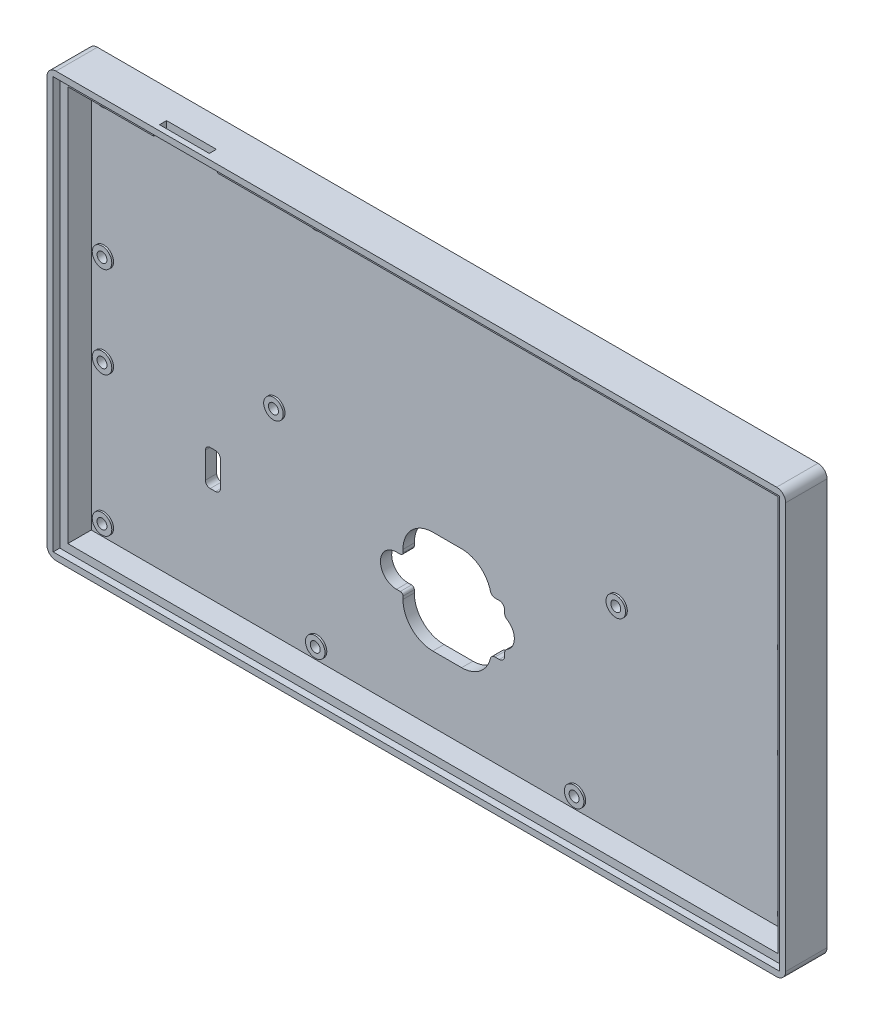
SolidWorks part; units mm, degrees
ref_plane "Front Plane" through (0, 0, 0) normal (0, 0, 1) x (1, 0, 0)
ref_plane "Top Plane" through (0, 0, 0) normal (0, 1, 0) x (1, 0, 0)
ref_plane "Right Plane" through (0, 0, 0) normal (1, 0, 0) x (0, 0, -1)
sketch "PCB" plane through (0, 0, 0) normal (0, 0, 1) x (1, 0, 0)
  line L0 (96.2635, 52.0314) -> (101.8921, 52.0314) construction
  line L1 (-101.8921, 57.66) -> (101.8921, 57.66) construction
  line L2 (-101.8921, 57.66) -> (-101.8921, -57.66) construction
  line L3 (-101.8921, -57.66) -> (101.8921, -57.66) construction
  line L4 (101.8921, 57.66) -> (101.8921, -57.66) construction
  line L5 (-101.8921, 57.66) -> (101.8921, -57.66) construction
  line L6 (-101.8921, -57.66) -> (101.8921, 57.66) construction
  line L7 (96.2635, 52.0314) -> (96.2635, 57.66) construction
  line L8 (-96.2635, 52.0314) -> (-101.8921, 52.0314) construction
  line L9 (-96.2635, -52.0314) -> (-96.2635, -57.66) construction
  line L10 (-92.8243, 0) -> (-92.8243, 32.1584) construction
  line L11 (-98.8568, 38.1909) -> (-86.7918, 38.1909)
  line L12 (-98.8568, 38.1909) -> (-98.8568, 26.1259)
  line L13 (-98.8568, 26.1259) -> (-86.7918, 26.1259)
  line L14 (-86.7918, 38.1909) -> (-86.7918, 26.1259)
  line L15 (-98.8568, 38.1909) -> (-86.7918, 26.1259) construction
  line L16 (-98.8568, 26.1259) -> (-86.7918, 38.1909) construction
  line L17 (-98.8568, 6.0325) -> (-86.7918, 6.0325)
  line L18 (-98.8568, 6.0325) -> (-98.8568, -6.0325)
  line L19 (-98.8568, -6.0325) -> (-86.7918, -6.0325)
  line L20 (-86.7918, 6.0325) -> (-86.7918, -6.0325)
  line L21 (-98.8568, 6.0325) -> (-86.7918, -6.0325) construction
  line L22 (-98.8568, -6.0325) -> (-86.7918, 6.0325) construction
  line L23 (-98.8568, -26.1259) -> (-86.7918, -26.1259)
  line L24 (-98.8568, -26.1259) -> (-98.8568, -38.1909)
  line L25 (-98.8568, -38.1909) -> (-86.7918, -38.1909)
  line L26 (-86.7918, -26.1259) -> (-86.7918, -38.1909)
  line L27 (-98.8568, -26.1259) -> (-86.7918, -38.1909) construction
  line L28 (-98.8568, -38.1909) -> (-86.7918, -26.1259) construction
  line L29 (86.7918, 38.1909) -> (98.8568, 38.1909)
  line L30 (86.7918, 38.1909) -> (86.7918, 26.1259)
  line L31 (86.7918, 26.1259) -> (98.8568, 26.1259)
  line L32 (98.8568, 38.1909) -> (98.8568, 26.1259)
  line L33 (86.7918, 38.1909) -> (98.8568, 26.1259) construction
  line L34 (86.7918, 26.1259) -> (98.8568, 38.1909) construction
  line L35 (86.7918, 6.0325) -> (98.8568, 6.0325)
  line L36 (86.7918, 6.0325) -> (86.7918, -6.0325)
  line L37 (86.7918, -6.0325) -> (98.8568, -6.0325)
  line L38 (98.8568, 6.0325) -> (98.8568, -6.0325)
  line L39 (86.7918, 6.0325) -> (98.8568, -6.0325) construction
  line L40 (86.7918, -6.0325) -> (98.8568, 6.0325) construction
  line L41 (86.7918, -26.1259) -> (98.8568, -26.1259)
  line L42 (86.7918, -26.1259) -> (86.7918, -38.1909)
  line L43 (86.7918, -38.1909) -> (98.8568, -38.1909)
  line L44 (98.8568, -26.1259) -> (98.8568, -38.1909)
  line L45 (86.7918, -26.1259) -> (98.8568, -38.1909) construction
  line L46 (86.7918, -38.1909) -> (98.8568, -26.1259) construction
  line L47 (-92.8243, 0) -> (-92.8243, -32.1584) construction
  line L48 (-92.8243, 32.1584) -> (-101.8921, 32.1584) construction
  line L49 (92.8243, 32.1584) -> (101.8921, 32.1584) construction
  line L50 (-3.114, -17.4952) -> (-3.114, -27.7568) construction
  circle A0 centre (-96.2635, 52.0314) radius 0.9995
  circle A1 centre (-96.2635, -52.0314) radius 0.9995
  circle A2 centre (96.2635, -52.0314) radius 0.9995
  circle A3 centre (96.2635, 52.0314) radius 0.9995
  circle A4 centre (-3.114, -17.4952) radius 1.9939
  circle A5 centre (-3.114, -27.7568) radius 1.9939
  point P0 (0, 0)
  point P14 (-92.8243, 32.1584)
  point P23 (-92.8243, 0)
  point P28 (-92.8243, -32.1584)
  point P33 (92.8243, 32.1584)
  point P38 (92.8243, 0)
  point P43 (92.8243, -32.1584)
  point P54 (0.1092, -22.626)
  point P55 (-7.5006, -22.626)
  point P60 (-3.114, -22.626)
  dimension "D4" = 1.999
  dimension "D14" = 3.9878
  dimension "D1" = 203.7842
  dimension "D2" = 115.32
  dimension "D3" = 5.6286
  dimension "D5" = 25.5016
  dimension "D6" = 25.5016
  dimension "D7" = 9.0678
  dimension "D8" = 12.065
  dimension "D9" = 102.0013
  dimension "D10" = 35.034
  dimension "D11" = 7.6098
  dimension "D12" = 5.1308
  dimension "D13" = 3.2233
sketch "DT_plug" plane through (0, 0, 0) normal (0, 0, 1) x (1, 0, 0)
  line L0 (29.2774, -40.0231) -> (29.2774, -5.0981) construction
  dimension "D1" = 34.925
sketch "display_screen" plane through (0, 0, 0) normal (0, 0, 1) x (1, 0, 0)
  line L1 (-80.3275, 46.3296) -> (83.7565, 46.3296) construction
  line L2 (-80.3275, 46.3296) -> (-80.3275, -50.9016) construction
  line L3 (-80.3275, -50.9016) -> (83.7565, -50.9016) construction
  line L4 (83.7565, 46.3296) -> (83.7565, -50.9016) construction
  line L5 (-78.2955, 44.2976) -> (78.2955, 44.2976) construction
  line L6 (-78.2955, 44.2976) -> (-78.2955, -44.2976) construction
  line L7 (-78.2955, -44.2976) -> (78.2955, -44.2976) construction
  line L8 (78.2955, 44.2976) -> (78.2955, -44.2976) construction
  point P8 (0, 44.2976)
  point P10 (-78.2955, 0)
  dimension "D1" = 164.084
  dimension "D2" = 97.2312
  dimension "D3" = 6.604
  dimension "D4" = 2.032
  dimension "D5" = 2.032
  dimension "D6" = 5.461
ref_plane "back_of_PCB" through (0, 0, -1.8542) normal (0, 0, 1) x (1, 0, 0)
ref_plane "back_PCB_clearance" through (0, 0, -8.4582) normal (0, 0, 1) x (1, 0, 0)
sketch "Sketch4" plane through (0, 0, 0) normal (0, 0, 1) x (1, 0, 0)
  line L0 (-102.1461, 57.8886) -> (-102.1461, 59.6386) construction
  line L1 (-102.1461, 57.8886) -> (102.1461, 57.8886)
  line L2 (-102.1461, 57.8886) -> (-102.1461, -57.8886)
  line L3 (-102.1461, -57.8886) -> (102.1461, -57.8886)
  line L4 (102.1461, 57.8886) -> (102.1461, -57.8886)
  line L5 (-103.8961, 59.6386) -> (103.8961, 59.6386)
  line L6 (-103.8961, 59.6386) -> (-103.8961, -59.6386)
  line L7 (-103.8961, -59.6386) -> (103.8961, -59.6386)
  line L8 (103.8961, 59.6386) -> (103.8961, -59.6386)
  line L9 (-102.1461, 57.8886) -> (-103.8961, 57.8886) construction
  line L10 (102.1461, -57.8886) -> (102.1461, -59.6386) construction
  line L11 (102.1461, -57.8886) -> (103.8961, -57.8886) construction
  line L12 (-101.8921, 57.66) -> (101.8921, 57.66) construction
  line L13 (-101.8921, 57.66) -> (-101.8921, -57.66) construction
  line L14 (101.8921, 57.66) -> (101.8921, -57.66) construction
  line L15 (-101.8921, -57.66) -> (101.8921, -57.66) construction
  dimension "D1" = 1.75
  dimension "D2" = 0.2286
  dimension "D3" = 0.254
  dimension "D4" = 0.254
  dimension "D5" = 0.2286
extrude "Boss-Extrude1" add sketch "Sketch4" against normal up to surface (1.8542 mm away) up to plane "back_of_PCB"
sketch "Sketch5" plane through (0, 0, -1.8542) normal (0, 0, -1) x (-1, 0, 0)
  line L1 (-103.8961, 59.6386) -> (103.8961, 59.6386)
  line L2 (-103.8961, 59.6386) -> (-103.8961, -59.6386)
  line L3 (-103.8961, -59.6386) -> (103.8961, -59.6386)
  line L4 (103.8961, 59.6386) -> (103.8961, -59.6386)
  line L6 (101.8921, 57.66) -> (-101.8921, 57.66) construction
  line L7 (-99.8931, 55.661) -> (99.8931, 55.661)
  line L8 (-99.8931, 55.661) -> (-99.8931, -55.661)
  line L9 (-99.8931, -55.661) -> (99.8931, -55.661)
  line L10 (99.8931, 55.661) -> (99.8931, -55.661)
  line L11 (-99.8931, 55.661) -> (-99.8931, 57.66) construction
  line L12 (-99.8931, 55.661) -> (-101.8921, 55.661) construction
  line L13 (-101.8921, 57.66) -> (-101.8921, -57.66) construction
  line L14 (99.8931, -55.661) -> (101.8921, -55.661) construction
  line L15 (101.8921, 57.66) -> (101.8921, -57.66) construction
  line L16 (99.8931, -55.661) -> (99.8931, -57.66) construction
  line L17 (101.8921, -57.66) -> (-101.8921, -57.66) construction
  dimension "D1" = 1.999
extrude "Boss-Extrude2" add sketch "Sketch5" along normal up to surface (6.604 mm away) up to plane "back_PCB_clearance"
sketch "Sketch6" plane through (0, 0, -8.4582) normal (0, 0, -1) x (-1, 0, 0)
  line L0 (11.7018, -27.9219) -> (11.7018, -28.722) construction
  line L1 (-103.8961, 59.6386) -> (103.8961, 59.6386)
  line L2 (-103.8961, 59.6386) -> (-103.8961, -59.6386)
  line L3 (-103.8961, -59.6386) -> (103.8961, -59.6386)
  line L4 (103.8961, 59.6386) -> (103.8961, -59.6386)
  line L5 (3.8278, -8.656) -> (-4.2865, -8.656) construction
  line L6 (11.7018, -16.53) -> (11.7018, -17.3301) construction
  line L7 (3.8278, -36.596) -> (-4.2865, -36.596) construction
  line L11 (12.9718, -18.6001) -> (14.0259, -18.6001) construction
  line L13 (12.9718, -26.6519) -> (14.0259, -26.6519) construction
  line L15 (-13.6655, -15.9585) -> (-14.8666, -15.9585) construction
  line L16 (-15.8826, -27.4459) -> (-15.8826, -28.2775) construction
  line L17 (-13.6655, -29.2935) -> (-14.8666, -29.2935) construction
  line L18 (-15.8826, -16.9745) -> (-15.8826, -17.8061) construction
  line L20 (12.2098, -27.9219) -> (12.2098, -28.722)
  line L21 (3.8278, -37.104) -> (-4.2865, -37.104)
  line L22 (-13.6655, -29.8015) -> (-14.8666, -29.8015)
  line L23 (-16.3906, -27.4459) -> (-16.3906, -28.2775)
  line L24 (-16.3906, -16.9745) -> (-16.3906, -17.8061)
  line L25 (-13.6655, -15.4505) -> (-14.8666, -15.4505)
  line L26 (3.8278, -8.148) -> (-4.2865, -8.148)
  line L27 (12.2098, -16.53) -> (12.2098, -17.3301)
  line L28 (12.9718, -18.0921) -> (14.0259, -18.0921)
  line L29 (12.9718, -27.1599) -> (14.0259, -27.1599)
  arc A0 (-16.7989, -19.4311) -> (-16.7989, -25.8209) centre (-14.8666, -22.626) ccw construction
  arc A1 (12.9718, -18.6001) -> (11.7018, -17.3301) centre (12.9718, -17.3301) cw construction
  arc A2 (12.9718, -26.6519) -> (11.7018, -27.9219) centre (12.9718, -27.9219) ccw construction
  arc A3 (14.0259, -26.6519) -> (14.0259, -18.6001) centre (14.0259, -22.626) ccw construction
  arc A4 (11.7018, -28.722) -> (3.8278, -36.596) centre (3.8278, -28.722) cw construction
  arc A5 (11.7018, -16.53) -> (3.8278, -8.656) centre (3.8278, -16.53) ccw construction
  arc A6 (-4.2865, -8.656) -> (-11.9202, -14.5996) centre (-4.2865, -16.53) ccw construction
  arc A7 (-11.9202, -14.5996) -> (-13.6655, -15.9585) centre (-13.6655, -14.1583) cw construction
  arc A8 (-4.2865, -36.596) -> (-11.9202, -30.6524) centre (-4.2865, -28.722) cw construction
  arc A9 (-11.9202, -30.6524) -> (-13.6655, -29.2935) centre (-13.6655, -31.0937) ccw construction
  arc A10 (-14.8666, -15.9585) -> (-15.8826, -16.9745) centre (-14.8666, -16.9745) ccw construction
  arc A11 (-15.8826, -17.8061) -> (-16.7989, -19.4311) centre (-17.7817, -17.8061) cw construction
  arc A12 (-15.8826, -27.4459) -> (-16.7989, -25.8209) centre (-17.7817, -27.4459) ccw construction
  arc A13 (-15.8826, -28.2775) -> (-14.8666, -29.2935) centre (-14.8666, -28.2775) ccw construction
  arc A14 (12.2098, -28.722) -> (3.8278, -37.104) centre (3.8278, -28.722) cw
  arc A15 (-4.2865, -37.104) -> (-12.4127, -30.7769) centre (-4.2865, -28.722) cw
  arc A16 (-12.4127, -30.7769) -> (-13.6655, -29.8015) centre (-13.6655, -31.0937) ccw
  arc A17 (-16.3906, -28.2775) -> (-14.8666, -29.8015) centre (-14.8666, -28.2775) ccw
  arc A18 (-16.3906, -27.4459) -> (-17.0618, -26.2556) centre (-17.7817, -27.4459) ccw
  arc A19 (-17.0618, -18.9964) -> (-17.0618, -26.2556) centre (-14.8666, -22.626) ccw
  arc A20 (-16.3906, -17.8061) -> (-17.0618, -18.9964) centre (-17.7817, -17.8061) cw
  arc A21 (-14.8666, -15.4505) -> (-16.3906, -16.9745) centre (-14.8666, -16.9745) ccw
  arc A22 (-12.4127, -14.4751) -> (-13.6655, -15.4505) centre (-13.6655, -14.1583) cw
  arc A23 (-4.2865, -8.148) -> (-12.4127, -14.4751) centre (-4.2865, -16.53) ccw
  arc A24 (12.2098, -16.53) -> (3.8278, -8.148) centre (3.8278, -16.53) ccw
  arc A25 (12.9718, -18.0921) -> (12.2098, -17.3301) centre (12.9718, -17.3301) cw
  arc A26 (14.0259, -27.1599) -> (14.0259, -18.0921) centre (14.0259, -22.626) ccw
  arc A27 (12.9718, -27.1599) -> (12.2098, -27.9219) centre (12.9718, -27.9219) ccw
  point P6 (-0.1092, -22.626)
  point P18 (0, 0)
  dimension "D7" = 3.7338
  dimension "D9" = 1.27
  dimension "D3" = 1.0541
  dimension "D10" = 7.874
  dimension "D13" = 1.8002
  dimension "D16" = 1.016
  dimension "D17" = 1.8991
  dimension "D2" = 11.811
  dimension "D4" = 13.97
  dimension "D5" = 15.7734
  dimension "D6" = 6.6675
  dimension "D8" = 1.016
  dimension "D11" = 0.8001
  dimension "D12" = 13.97
  dimension "D14" = 8.1143
  dimension "D15" = 6.6675
  dimension "D22" = 0.508
extrude "Boss-Extrude3" add sketch "Sketch6" along normal blind 3.175
sketch "mounting_bolt_pattern" plane through (0, 0, -11.6332) normal (0, 0, -1) x (-1, 0, 0)
  line L0 (-38.1, 22.225) -> (38.1, 22.225) construction
  line L1 (38.1, 22.225) -> (38.1, -22.225) construction
  line L3 (38.1, 22.225) -> (38.1, 59.6386) construction
  line L4 (-103.8961, 59.6386) -> (103.8961, 59.6386) construction
  line L5 (38.1, -22.225) -> (38.1, -59.6386) construction
  line L6 (103.8961, -59.6386) -> (-103.8961, -59.6386) construction
  circle A0 centre (-38.1, 22.225) radius 2.032
  circle A1 centre (-38.1, 22.225) radius 5.207 construction
  circle A2 centre (-38.1, -22.225) radius 5.207 construction
  circle A3 centre (-38.1, -22.225) radius 2.032
  circle A4 centre (38.1, -22.225) radius 2.032
  circle A5 centre (38.1, -22.225) radius 5.207 construction
  circle A6 centre (38.1, 22.225) radius 2.032
  circle A7 centre (38.1, 22.225) radius 5.207 construction
  point P12 (0, 22.225)
  dimension "D1" = 4.064
  dimension "D2" = 3.175
  dimension "D3" = 76.2
  dimension "D4" = 44.45
fillet "Fillet1" radius 2.54 4 edges at (103.8961, 59.6386, -5.8166) (103.8961, -59.6386, -5.8166) (-103.8961, -59.6386, -5.8166) (-103.8961, 59.6386, -5.8166)
sketch "Sketch11" plane through (0, 0, -8.4582) normal (0, 0, 1) x (1, 0, 0)
  line L0 (-96.377, 52.1375) -> (-96.377, 57.8886) construction
  line L1 (-96.377, 52.1375) -> (96.377, 52.1375) construction
  line L2 (-96.377, 52.1375) -> (-96.377, -52.1375) construction
  line L3 (-96.377, -52.1375) -> (96.377, -52.1375) construction
  line L4 (96.377, 52.1375) -> (96.377, -52.1375) construction
  line L5 (-102.1461, 57.8886) -> (102.1461, 57.8886) construction
  line L6 (-96.377, 52.1375) -> (-102.1461, 52.1375) construction
  line L7 (-102.1461, 57.8886) -> (-102.1461, -57.8886) construction
  line L8 (96.377, -52.1375) -> (102.1461, -52.1375) construction
  line L9 (102.1461, -57.8886) -> (102.1461, 57.8886) construction
  line L10 (96.377, -52.1375) -> (96.377, -57.8886) construction
  line L11 (102.1461, -57.8886) -> (-102.1461, -57.8886) construction
  circle A0 centre (-96.377, 52.1375) radius 1.4
  circle A2 centre (96.377, 52.1375) radius 1.4
  circle A3 centre (-96.377, -52.1375) radius 1.4
  circle A4 centre (96.377, -52.1375) radius 1.4
  circle A5 centre (96.377, -12.8125) radius 1.4
  circle A6 centre (96.377, 12.8125) radius 1.4
  circle A8 centre (-96.377, -12.8125) radius 1.4
  circle A9 centre (-96.377, 12.8125) radius 1.4
  circle A10 centre (-36.393, 52.1375) radius 1.4
  circle A11 centre (36.427, 52.1375) radius 1.4
  circle A12 centre (36.427, -52.1375) radius 1.4
  circle A13 centre (-36.393, -52.1375) radius 1.4
  circle A14 centre (-48.148, 0.0375) radius 1.4
  circle A15 centre (48.148, 0.0375) radius 1.4
  point P17 (0, 0)
  dimension "D3" = 2.8
  dimension "D1" = 104.275
  dimension "D2" = 192.754
  dimension "D4" = 59.984
  dimension "D5" = 59.95
  dimension "D6" = 39.325
  dimension "D7" = 39.325
  dimension "D8" = 48.229
  dimension "D9" = 52.1
  dimension "D10" = 48.229
extrude "Cut-Extrude2" cut sketch "Sketch11" against normal up to next
sketch "Sketch12" plane through (0, 59.6386, 0) normal (0, 1, 0) x (1, 0, 0)
  line L0 (101.3561, 0) -> (-101.3561, 0) construction
  line L1 (-73.7461, 3.5) -> (-59.7461, 3.5)
  line L2 (-73.7461, 3.5) -> (-73.7461, 1.5)
  line L3 (-73.7461, 1.5) -> (-59.7461, 1.5)
  line L4 (-59.7461, 3.5) -> (-59.7461, 1.5)
  line L6 (-103.8961, 0) -> (-103.8961, 11.6332) construction
  dimension "D1" = 1.5
  dimension "D2" = 14
  dimension "D3" = 30.15
  dimension "D4" = 2
extrude "Cut-Extrude3" cut sketch "Sketch12" against normal up to next
sketch "Sketch13" plane through (0, 0, -1.8542) normal (0, 0, 1) x (1, 0, 0)
  line L0 (-59.7461, 57.8886) -> (102.1461, 57.8886) construction
  line L1 (-75.7461, 55.661) -> (-57.7461, 55.661)
  line L2 (-75.7461, 55.661) -> (-75.7461, 57.8886)
  line L3 (-75.7461, 57.8886) -> (-57.7461, 57.8886)
  line L4 (-57.7461, 55.661) -> (-57.7461, 57.8886)
  line L5 (99.8931, 55.661) -> (-99.8931, 55.661) construction
  line L6 (-73.7461, 57.8886) -> (-73.7461, 55.661) construction
  line L7 (-59.7461, 55.661) -> (-59.7461, 59.6386) construction
  dimension "D1" = 2
  dimension "D2" = 2
extrude "Cut-Extrude4" cut sketch "Sketch13" against normal up to surface (1.6458 mm away) up to face at (-66.7461, 57.6498, -3.5)
sketch "Sketch14" plane through (0, 0, -8.4582) normal (0, 0, 1) x (1, 0, 0)
  circle A0 centre (-96.377, 52.1375) radius 1.4
  circle A1 centre (-96.377, 52.1375) radius 2.75
  circle A3 centre (-96.377, 52.1375) radius 1.4 construction
  circle A4 centre (-36.393, 52.1375) radius 2.75
  circle A5 centre (-36.393, 52.1375) radius 1.4
  circle A8 centre (36.427, 52.1375) radius 1.4
  circle A9 centre (36.427, 52.1375) radius 2.75
  circle A10 centre (96.377, 52.1375) radius 1.4
  circle A11 centre (96.377, 52.1375) radius 2.75
  circle A12 centre (-96.377, 12.8125) radius 1.4
  circle A13 centre (-96.377, 12.8125) radius 2.75
  circle A14 centre (-48.148, 0.0375) radius 1.4
  circle A15 centre (-48.148, 0.0375) radius 2.75
  circle A16 centre (-96.377, -12.8125) radius 1.4
  circle A17 centre (-96.377, -12.8125) radius 2.75
  circle A18 centre (-96.377, -52.1375) radius 1.4
  circle A19 centre (-96.377, -52.1375) radius 2.75
  circle A20 centre (-36.393, -52.1375) radius 1.4
  circle A21 centre (-36.393, -52.1375) radius 2.75
  circle A24 centre (48.148, 0.0375) radius 1.4
  circle A25 centre (48.148, 0.0375) radius 2.75
  circle A26 centre (36.427, -52.1375) radius 1.4
  circle A27 centre (36.427, -52.1375) radius 2.75
  circle A28 centre (96.377, -52.1375) radius 1.4
  circle A29 centre (96.377, -52.1375) radius 2.75
  circle A30 centre (96.377, -12.8125) radius 1.4
  circle A31 centre (96.377, -12.8125) radius 2.75
  circle A32 centre (96.377, 12.8125) radius 1.4
  circle A33 centre (96.377, 12.8125) radius 2.75
  circle A34 centre (-36.393, 52.1375) radius 1.4 construction
  circle A36 centre (36.427, 52.1375) radius 1.4 construction
  circle A37 centre (96.377, 52.1375) radius 1.4 construction
  circle A38 centre (96.377, 12.8125) radius 1.4 construction
  circle A39 centre (48.148, 0.0375) radius 1.4 construction
  circle A40 centre (-48.148, 0.0375) radius 1.4 construction
  circle A41 centre (-96.377, 12.8125) radius 1.4 construction
  circle A42 centre (-96.377, -12.8125) radius 1.4 construction
  circle A43 centre (-96.377, -52.1375) radius 1.4 construction
  circle A44 centre (-36.393, -52.1375) radius 1.4 construction
  circle A46 centre (36.427, -52.1375) radius 1.4 construction
  circle A47 centre (96.377, -52.1375) radius 1.4 construction
  circle A48 centre (96.377, -12.8125) radius 1.4 construction
  dimension "D1" = 5.5
extrude "Boss-Extrude4" add sketch "Sketch14" along normal blind 0.5
sketch "Sketch15" plane through (0, 0, -8.4582) normal (0, 0, 1) x (1, 0, 0)
  line L0 (-99.8931, 55.661) -> (-99.8931, -55.661) construction
  line L1 (-66.4371, -18.812) -> (-64.9371, -18.812)
  line L2 (-67.7871, -20.162) -> (-67.7871, -27.462)
  line L3 (-66.4371, -28.812) -> (-64.9371, -28.812)
  line L4 (-63.5871, -20.162) -> (-63.5871, -27.462)
  line L5 (-99.8931, -55.661) -> (99.8931, -55.661) construction
  arc A0 (-64.9371, -28.812) -> (-63.5871, -27.462) centre (-64.9371, -27.462) ccw
  arc A1 (-67.7871, -27.462) -> (-66.4371, -28.812) centre (-66.4371, -27.462) ccw
  arc A2 (-66.4371, -18.812) -> (-67.7871, -20.162) centre (-66.4371, -20.162) ccw
  arc A3 (-64.9371, -18.812) -> (-63.5871, -20.162) centre (-64.9371, -20.162) cw
  point P10 (-63.5871, -28.812)
  point P13 (-67.7871, -28.812)
  point P16 (-67.7871, -18.812)
  dimension "D5" = 1.35
  dimension "D1" = 32.106
  dimension "D2" = 4.2
  dimension "D3" = 10
  dimension "D4" = 26.849
extrude "Cut-Extrude5" cut sketch "Sketch15" against normal up to next
